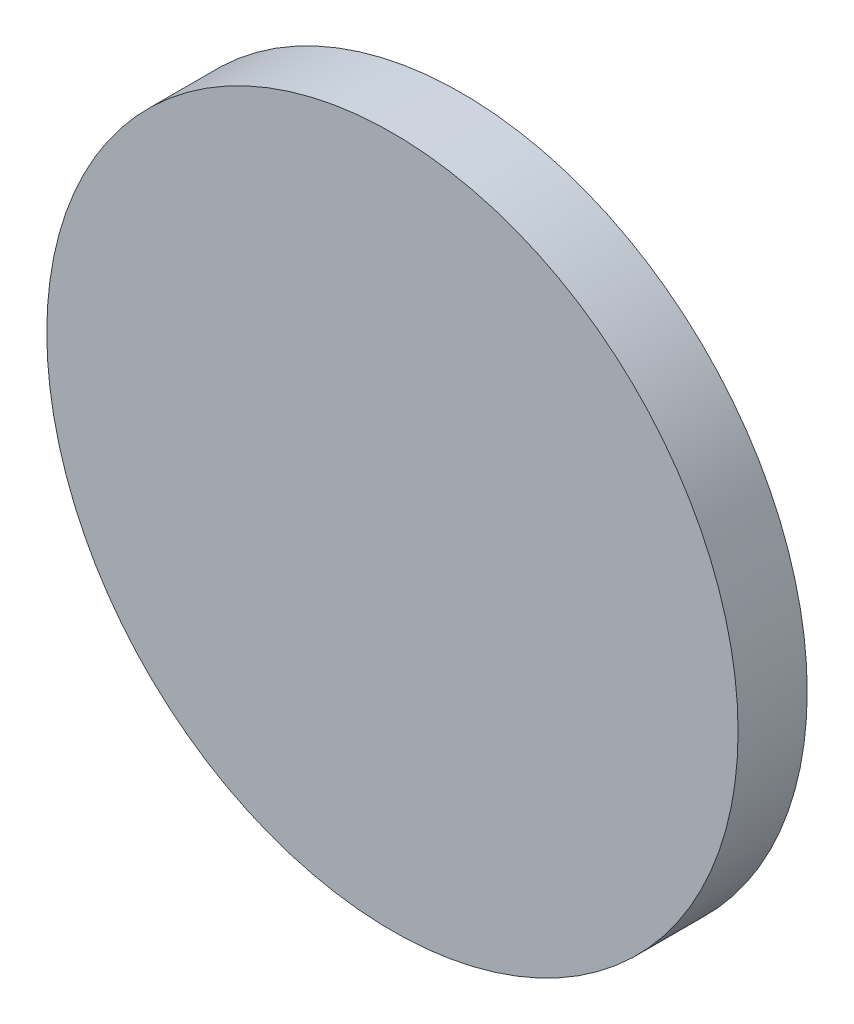
SolidWorks part; units mm, degrees
ref_plane "Front Plane" through (0, 0, 0) normal (0, 0, 1) x (1, 0, 0)
ref_plane "Top Plane" through (0, 0, 0) normal (0, 1, 0) x (1, 0, 0)
ref_plane "Right Plane" through (0, 0, 0) normal (1, 0, 0) x (0, 0, -1)
sketch "Sketch1" plane through (0, 0, 0) normal (0, 0, 1) x (1, 0, 0)
  circle A0 centre (0, 0) radius 80
  dimension "D1" = 160
extrude "Boss-Extrude1" add sketch "Sketch1" along normal blind 16
